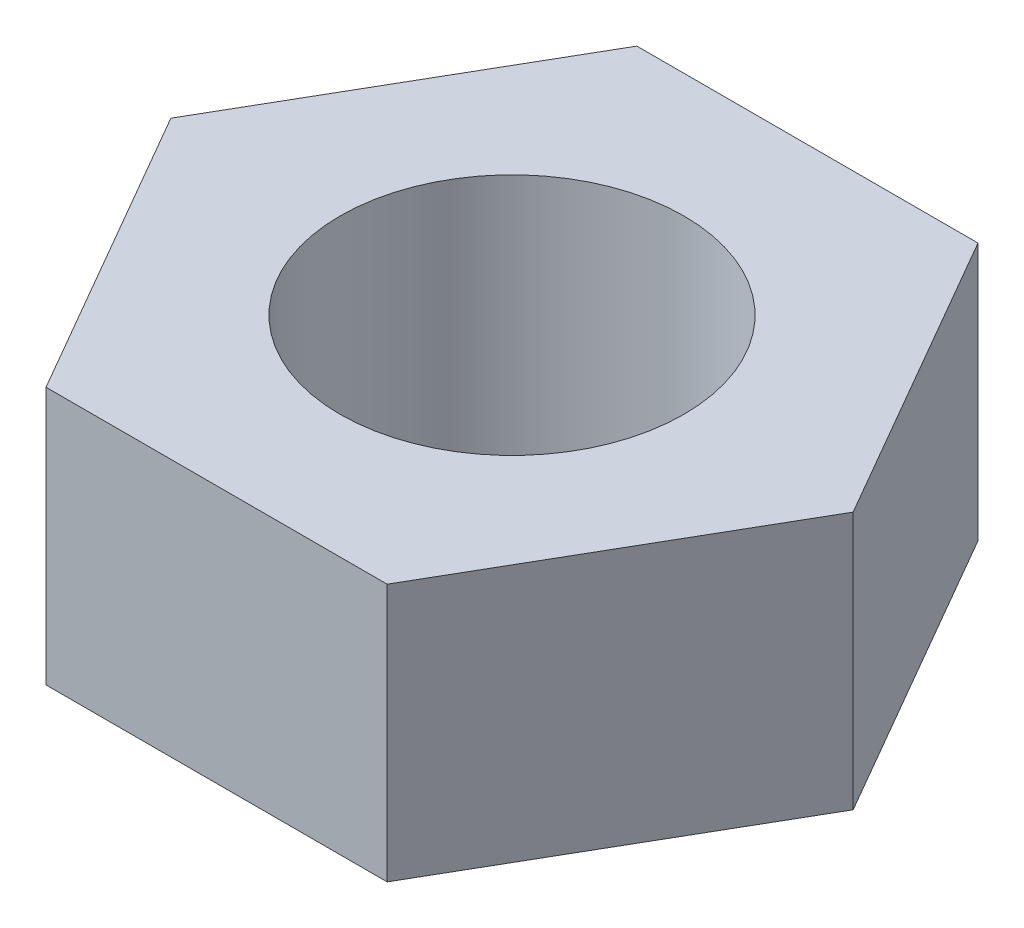
SolidWorks part; units mm, degrees
other "Frame Rear Nut Left"
ref_plane "Front Plane" through (0, 0, 0) normal (0, 0, 1) x (1, 0, 0)
ref_plane "Top Plane" through (0, 0, 0) normal (0, 1, 0) x (1, 0, 0)
ref_plane "Right Plane" through (0, 0, 0) normal (1, 0, 0) x (0, 0, -1)
sketch3d "Base Outline Sketch datum points"
  point P0 (0, 157.5, 0)
  point P1 (10, 157.5, 0)
  point P2 (0, 157.5, -10)
ref_plane "Base Outline Sketch plane" through (0, 157.5, 0) normal (0, 1, 0) x (1, 0, 0)
sketch "Base Outline Sketch" plane through (0, 157.5, 0) normal (0, 1, 0) x (1, 0, 0)
  line L0 (-54.7039, -52.75) -> (-53.1162, -50)
  line L1 (-57.8794, -52.75) -> (-54.7039, -52.75)
  line L2 (-53.1162, -50) -> (-54.7039, -47.25)
  line L3 (-54.7039, -47.25) -> (-57.8794, -47.25)
  line L4 (-59.4671, -50) -> (-57.8794, -52.75)
  line L5 (-57.8794, -47.25) -> (-59.4671, -50)
  circle A0 centre (-56.2917, -50) radius 1.6
extrude "Base Outline" add sketch "Base Outline Sketch" along normal blind 2.4 separate body
